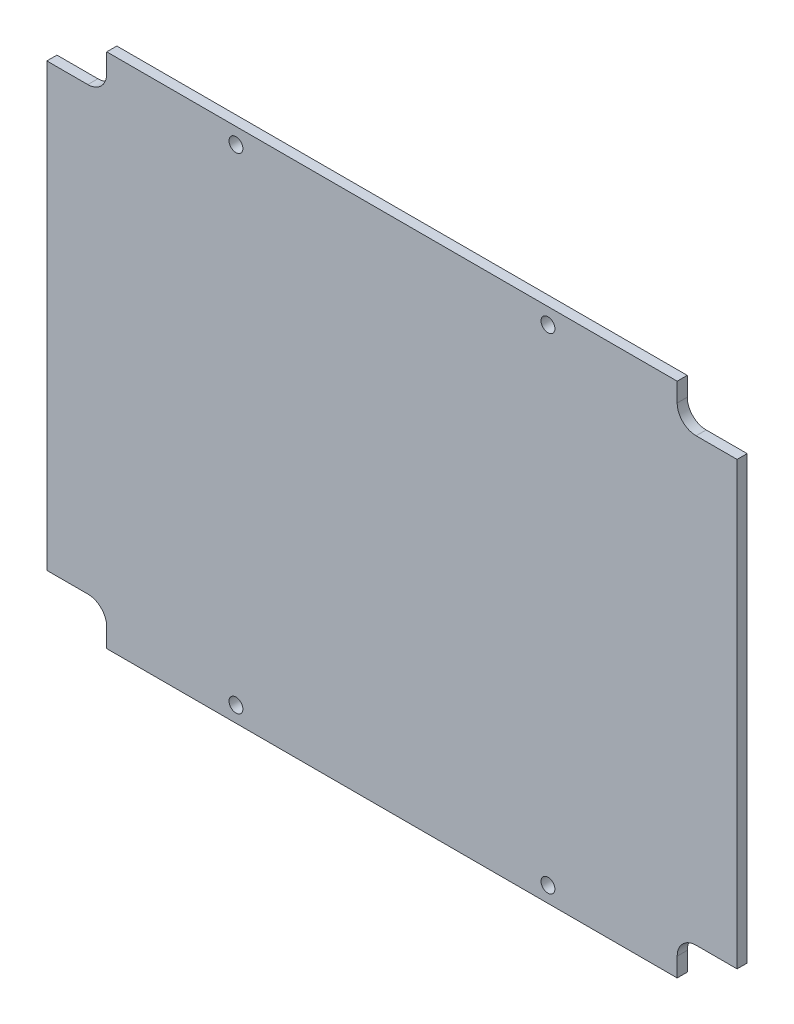
SolidWorks part; units mm, degrees
ref_plane "Front Plane" through (0, 0, 0) normal (0, 0, 1) x (1, 0, 0)
ref_plane "Top Plane" through (0, 0, 0) normal (0, 1, 0) x (1, 0, 0)
ref_plane "Right Plane" through (0, 0, 0) normal (1, 0, 0) x (0, 0, -1)
sketch "Sketch1" plane through (0, 0, 0) normal (0, 0, 1) x (1, 0, 0)
  line L0 (-55.4936, 9.9519) -> (-45.9936, 9.9519)
  line L1 (-45.9936, 85.9519) -> (44.5064, 85.9519)
  line L2 (54.0064, 79.9519) -> (54.0064, 9.9519)
  line L4 (-55.4936, 79.9519) -> (-55.4936, 9.9519)
  line L5 (-45.9936, 3.9519) -> (44.5064, 3.9519)
  line L6 (-45.9936, 9.9519) -> (-45.9936, 3.9519)
  line L7 (-55.4936, 79.9519) -> (-45.9936, 79.9519)
  line L8 (-45.9936, 79.9519) -> (-45.9936, 85.9519)
  line L9 (44.5064, 85.9519) -> (44.5064, 79.9519)
  line L10 (44.5064, 79.9519) -> (54.0064, 79.9519)
  line L11 (44.5064, 3.9519) -> (44.5064, 9.9519)
  line L12 (44.5064, 9.9519) -> (54.0064, 9.9519)
  circle A0 centre (-25.4936, 83.4519) radius 1.1
  circle A1 centre (24.0064, 83.4519) radius 1.1
  circle A2 centre (24.0064, 6.4519) radius 1.1
  circle A3 centre (-25.4936, 6.4519) radius 1.1
  dimension "D1" = 2.2
  dimension "D2" = 2.5
  dimension "D3" = 82
  dimension "D4" = 109.5
  dimension "D5" = 2.5
  dimension "D6" = 6
  dimension "D7" = 2.5
  dimension "D8" = 2.5
  dimension "D9" = 30
  dimension "D10" = 30
  dimension "D11" = 30
  dimension "D12" = 30
  dimension "D13" = 9.5
extrude "Boss-Extrude1" add sketch "Sketch1" along normal blind 1.6
fillet "Fillet1" radius 3 4 edges at (-45.9936, 9.9519, 0.8) (44.5064, 9.9519, 0.8) (44.5064, 79.9519, 0.8) (-45.9936, 79.9519, 0.8)
